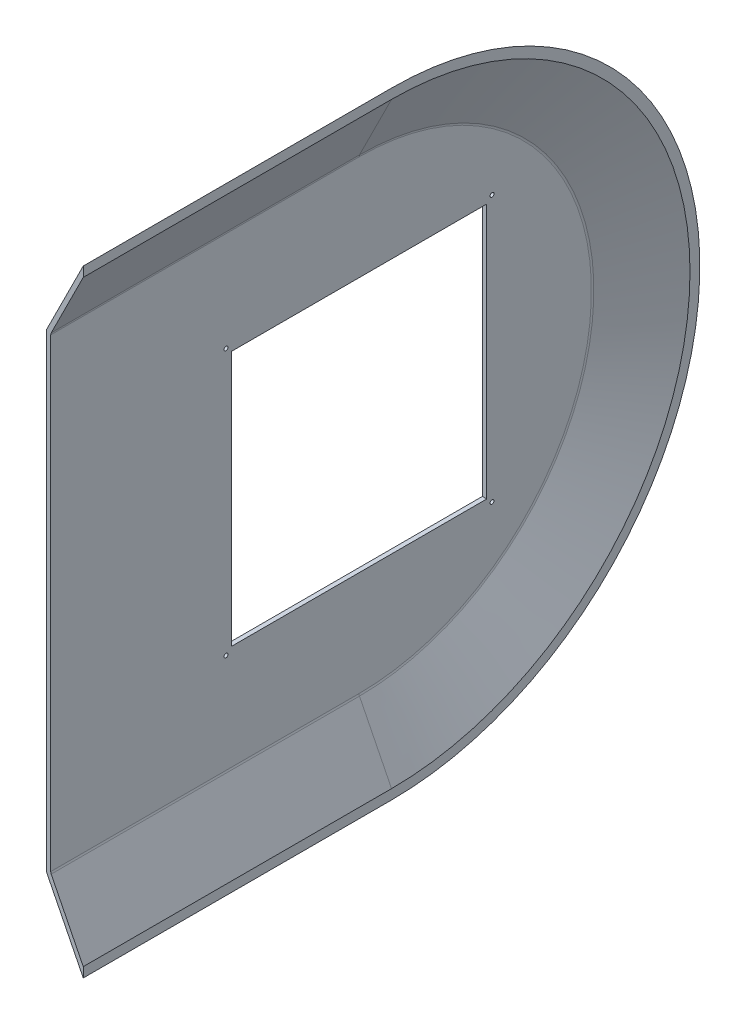
SolidWorks part; units mm, degrees
material "Brass"
ref_plane "Plan de face" through (0, 0, 0) normal (0, 0, 1) x (1, 0, 0)
ref_plane "Plan de dessus" through (0, 0, 0) normal (0, 1, 0) x (1, 0, 0)
ref_plane "Plan de droite" through (0, 0, 0) normal (1, 0, 0) x (0, 0, -1)
sketch "Esquisse2" plane through (0, 0, 0) normal (0, 0, 1) x (1, 0, 0)
  line L0 (41.9268, 350) -> (41.9268, 0)
  line L5 (0, 266.1905) -> (41.9268, 350)
  line L6 (41.9268, 0) -> (0, 0)
  line L8 (0, 266.1905) -> (0, 0)
  dimension "D1" = 266.1905
  dimension "D2" = 350
  dimension "D3" = 153.423
  dimension "D4" = 90
revolve "Revolve1" add sketch "Esquisse2" angle 180 about L6
sketch "Sketch5" plane through (0, 0, 0) normal (0, 0, 1) x (1, 0, 0)
  line L3 (41.9268, 350) -> (0, 266.1905) construction
  line L4 (0, 266.1905) -> (41.9268, 350)
  line L5 (0, 266.1905) -> (0, -266.1905)
  line L6 (0, -266.1905) -> (41.9268, -350)
  line L7 (41.9268, -350) -> (41.9268, 350)
extrude "Boss-Extrude1" add sketch "Sketch5" along normal blind 350 contours L5 L6 L7 L4
shell "Shell2" thickness 5
sketch "Sketch4" plane through (0, 0, 0) normal (-1, 0, 0) x (0, 0, 1)
  line L0 (0, -55) -> (0, 55) construction
  line L1 (-145, 145) -> (145, 145)
  line L2 (-145, 145) -> (-145, -145)
  line L3 (-145, -145) -> (145, -145)
  line L4 (145, 145) -> (145, -145)
  dimension "D1" = 290
  dimension "D2" = 290
  dimension "D3" = 145
  dimension "D4" = 145
extrude "Cut-Extrude1" cut sketch "Sketch4" against normal through all
sketch "Sketch7" plane through (0, 0, 0) normal (0, 0, 1) x (1, 0, 0)
  line L0 (0, 0) -> (75.7734, 0) construction
sketch "Sketch8" plane through (0, 0, 0) normal (-1, 0, 0) x (0, 0, 1)
  line L1 (-151, 151) -> (151, 151)
  line L2 (-151, 151) -> (-151, -151)
  line L3 (-151, -151) -> (151, -151)
  line L4 (151, 151) -> (151, -151)
  point P4 (0, 151)
  point P6 (151, 0)
  dimension "D1" = 302
  dimension "D2" = 302
  dimension "D3" = 0
  dimension "D4" = 0
hole_wizard "M4 Clearance Hole1" positions "Sketch11" profile "Sketch10" hole size "M4" standard "ANSI Metric"
sketch "Sketch11" plane through (0, 0, 0) normal (-1, 0, 0) x (0, 0, 1)
  point P2 (151, 151)
  point P5 (151, -151)
  point P8 (-151, -151)
  point P11 (-151, 151)
sketch "Sketch10" plane through (0, 151, 151) normal (0, 1, 0) x (0, 0, 1)
  line L0 (0, 0) -> (0, 31.3519)
  line L1 (0, 31.3519) -> (2.25, 30)
  line L2 (2.25, 30) -> (2.25, 0)
  line L5 (2.25, 0) -> (0, 0)
  line L10 (0, 31.3519) -> (-2.25, 30) construction
  line L11 (0, -6.35) -> (0, 107.95) construction
  dimension "Hole Dia." = 4.5
  dimension "Hole Depth" = 30
  dimension "Drill Angle" = 118
fillet "Fillet1" radius 5 6 edges at (5, -265.0097, 175) (5, 0, -265.0097) (5, 265.0097, 175) (0, -266.1905, 175) (0, 0, -266.1905) (0, 266.1905, 175)
equation "\"D3@Sketch4\"=\"D2@Sketch4\"/2"
equation "\"D4@Sketch4\"=\"D1@Sketch4\"/2"
